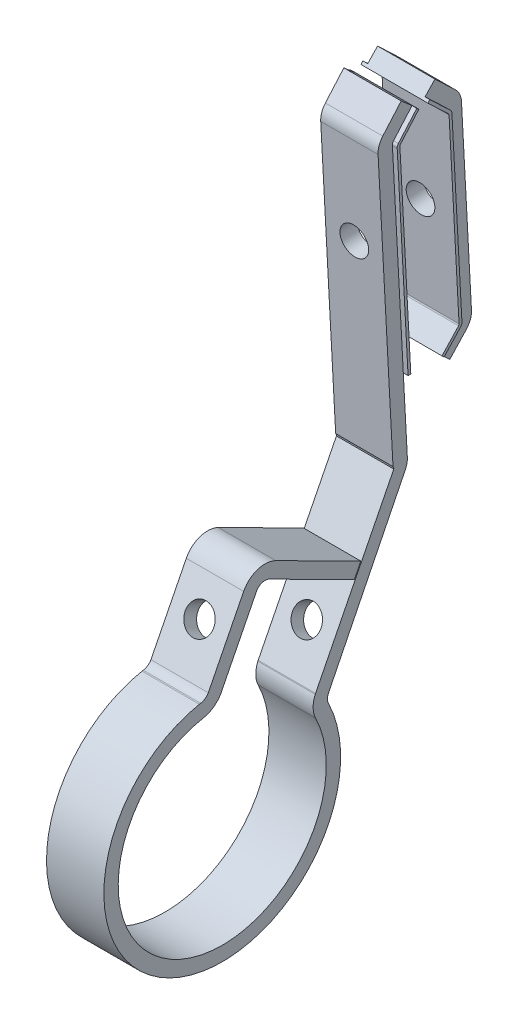
SolidWorks part; units mm, degrees
material "1.4003 (X2CrNi12)"
ref_plane "Ön Düzlem" through (0, 0, 0) normal (0, 0, 1) x (1, 0, 0)
ref_plane "Üst Düzlem" through (0, 0, 0) normal (0, 1, 0) x (1, 0, 0)
ref_plane "Sağ Düzlem" through (0, 0, 0) normal (1, 0, 0) x (0, 0, -1)
sketch "Çizim1" plane through (0, 0, 0) normal (1, 0, 0) x (0, 0, -1)
  line L0 (39.7037, 110.5306) -> (35.8427, 106.0936)
  line L1 (35.5986, 105.3835) -> (38.7268, 47.2558)
  line L2 (37.4406, 112.4999) -> (39.7037, 110.5306)
  line L3 (35.8917, 46.5826) -> (19.5215, 14.1278)
  line L4 (42.43, 110.7581) -> (46.7449, 106.6514)
  line L5 (47.054, 105.9808) -> (49.1474, 67.0901)
  line L6 (48.8812, 66.3554) -> (45.416, 62.6286)
  line L7 (45.416, 62.6286) -> (47.613, 60.5858)
  line L8 (44.4983, 112.9312) -> (42.43, 110.7581)
  line L9 (4.4816, 40.1211) -> (-2.9199, 25.4473)
  line L10 (27.6426, 30.6787) -> (9.8466, 39.6551)
  line L11 (7.1602, 38.7701) -> (-0.2413, 24.0962)
  line L12 (28.9937, 33.3573) -> (27.6426, 30.6787)
  line L13 (32.6029, 105.2222) -> (35.7311, 47.0946)
  line L14 (50.0497, 106.142) -> (52.1431, 67.2513)
  line L15 (38.3159, 45.2633) -> (22.2001, 12.7768)
  line L16 (28.9937, 33.3573) -> (11.1977, 42.3336)
  line L17 (51.0782, 64.3126) -> (47.613, 60.5858)
  line L18 (44.4983, 112.9312) -> (48.8132, 108.8245)
  line L19 (37.4406, 112.4999) -> (33.5796, 108.063)
  line L20 (19.5215, 14.1278) -> (19.4465, 13.9675)
  line L21 (-0.2413, 24.0962) -> (-0.3257, 23.9405)
  line L22 (-4.5331, 24.3487) -> (-4.7856, 24.3004)
  arc A0 (48.8132, 108.8245) -> (50.0497, 106.142) centre (46.0555, 105.927) cw
  arc A1 (32.6029, 105.2222) -> (33.5796, 108.063) centre (36.5971, 105.4372) cw
  arc A2 (51.0782, 64.3126) -> (52.1431, 67.2513) centre (48.1489, 67.0363) ccw
  arc A3 (35.5986, 105.3835) -> (35.8427, 106.0936) centre (36.5971, 105.4372) cw
  arc A4 (38.7268, 47.2558) -> (38.3159, 45.2633) centre (34.7325, 47.0409) cw
  arc A5 (35.7311, 47.0946) -> (35.8917, 46.5826) centre (34.8923, 46.5502) cw
  arc A6 (46.7449, 106.6514) -> (47.054, 105.9808) centre (46.0555, 105.927) cw
  arc A7 (48.8812, 66.3554) -> (49.1474, 67.0901) centre (48.1489, 67.0363) ccw
  arc A8 (19.4465, 13.9675) -> (19.5078, 9.6566) centre (24.2733, 11.8803) ccw
  arc A9 (-2.9199, 25.4473) -> (-4.5331, 24.3487) centre (-4.873, 26.5817) cw
  arc A10 (-0.3257, 23.9405) -> (-3.8289, 21.4277) centre (-4.873, 26.5817) cw
  arc A11 (11.1977, 42.3336) -> (4.4816, 40.1211) centre (8.9459, 37.8694) ccw
  arc A12 (9.8466, 39.6551) -> (7.1602, 38.7701) centre (8.9459, 37.8694) ccw
  arc A13 (-3.8289, 21.4277) -> (19.5078, 9.6566) centre (0, 0) ccw
  arc A14 (-4.7856, 24.3004) -> (22.2755, 10.8265) centre (0, 0) ccw
  arc A15 (22.2001, 12.7768) -> (22.2755, 10.8265) centre (24.2733, 11.8803) ccw
extrude "Yükseklik-Ekstrüzyon1" add sketch "Çizim1" along normal blind 12
sketch "Çizim2" plane through (0, 0, 0) normal (1, 0, 0) x (0, 0, -1)
  line L0 (39.7037, 110.5306) -> (35.8427, 106.0936)
  line L1 (35.5986, 105.3835) -> (37.8789, 63.0106)
  line L2 (42.43, 110.7581) -> (46.7449, 106.6514)
  line L3 (47.054, 105.9808) -> (49.1474, 67.0901)
  line L4 (48.8812, 66.3554) -> (45.416, 62.6286)
  line L5 (42.0164, 110.3235) -> (46.3313, 106.2168)
  line L6 (46.4549, 105.9485) -> (48.5483, 67.0578)
  line L7 (48.4418, 66.764) -> (44.9766, 63.0372)
  line L8 (45.416, 62.6286) -> (44.9766, 63.0372)
  line L9 (42.0164, 110.3235) -> (42.43, 110.7581)
  line L10 (40.1337, 110.1564) -> (36.2727, 105.7195)
  line L11 (36.1677, 105.4141) -> (38.4497, 63.0106)
  line L12 (39.7037, 110.5306) -> (40.1337, 110.1564)
  line L13 (38.4497, 63.0106) -> (37.8789, 63.0106)
  arc A0 (35.5986, 105.3835) -> (35.8427, 106.0936) centre (36.5971, 105.4372) cw
  arc A1 (48.8812, 66.3554) -> (49.1474, 67.0901) centre (48.1489, 67.0363) ccw
  arc A2 (48.4418, 66.764) -> (48.5483, 67.0578) centre (48.1489, 67.0363) ccw
  arc A3 (36.1677, 105.4141) -> (36.2727, 105.7195) centre (36.5971, 105.4372) cw
  arc A4 (46.3313, 106.2168) -> (46.4549, 105.9485) centre (46.0555, 105.927) cw
  arc A5 (46.7449, 106.6514) -> (47.054, 105.9808) centre (46.0555, 105.927) cw
extrude "Yükseklik-Ekstrüzyon2" add sketch "Çizim2" along normal blind 13 and the other way blind 1
sketch "Çizim3" plane through (0, 2.9929, -55.602) normal (0, 0.0537, -0.9986) x (-1, 0, 0)
  line L0 (-12, 110.3762) -> (0, 110.3762) construction
  circle A0 centre (-6, 84.1062) radius 3
  dimension "D1" = 26.27
  dimension "D2" = 6
extrude "Kes-Ekstrüzyon1" cut sketch "Çizim3" against normal through all both and the other way through all
sketch "Çizim4" plane through (0, 6.3353, 12.56) normal (0, 0.4504, 0.8929) x (1, 0, 0)
  line L0 (12, 37.8405) -> (0, 37.8405) construction
  circle A0 centre (6, 30.6505) radius 3
  point P2 (6, 37.8405)
  dimension "D1" = 7.19
  dimension "D2" = 6
extrude "Kes-Ekstrüzyon2" cut sketch "Çizim4" against normal through all both and the other way through all
